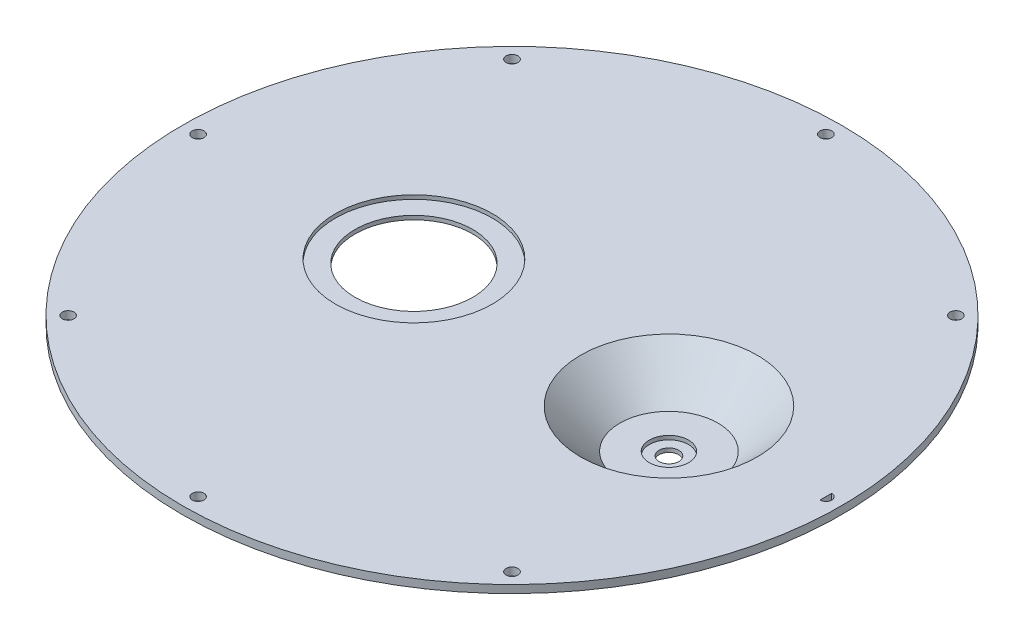
SolidWorks part; units mm, degrees
ref_plane "前视基准面" through (0, 0, 0) normal (0, 0, 1) x (1, 0, 0)
ref_plane "上视基准面" through (0, 0, 0) normal (0, 1, 0) x (1, 0, 0)
ref_plane "右视基准面" through (0, 0, 0) normal (1, 0, 0) x (0, 0, -1)
sketch "草图1" plane through (0, 0, 0) normal (0, 1, 0) x (1, 0, 0)
  circle A0 centre (0, 0) radius 84
  dimension "D1" = 168
extrude "凸台-拉伸1" add sketch "草图1" along normal blind 2
sketch "草图2" plane through (0, 2, 0) normal (0, 1, 0) x (1, 0, 0)
  circle A0 centre (0, 0) radius 80
  circle A1 centre (0, 80) radius 1.5
  circle A2 centre (0, 0) radius 80
  circle A3 centre (56.5685, 56.5685) radius 1.5
  circle A4 centre (0, 0) radius 80
  circle A5 centre (80, 0) radius 1.5
  circle A6 centre (0, 0) radius 80
  circle A7 centre (56.5685, -56.5685) radius 1.5
  circle A8 centre (0, 0) radius 80
  circle A9 centre (0, -80) radius 1.5
  circle A10 centre (0, 0) radius 80
  circle A11 centre (-56.5685, -56.5685) radius 1.5
  circle A12 centre (0, 0) radius 80
  circle A13 centre (-80, 0) radius 1.5
  circle A14 centre (0, 0) radius 80
  circle A15 centre (-56.5685, 56.5685) radius 1.5
  point P28 (0, 0)
  dimension "D1" = 160
  dimension "D2" = 3
  dimension "D3" = 8
extrude "切除-拉伸1" cut sketch "草图2" against normal blind 2 contours A1 | A3 | A5 | A7 | A9 | A11 | A13 | A15
sketch "草图3" plane through (0, 2, 0) normal (0, 1, 0) x (1, 0, 0)
  line L0 (0, 0) -> (40, 0)
  line L1 (0, 0) -> (-25, 0)
  circle A0 centre (-25, 0) radius 15
  circle A1 centre (40, 0) radius 22.5
  dimension "D3" = 30
  dimension "D4" = 45
  dimension "D1" = 40
  dimension "D2" = 25
extrude "切除-拉伸2" cut sketch "草图3" against normal blind 2
sketch "草图4" plane through (0, 2, 0) normal (0, 1, 0) x (1, 0, 0)
  circle A0 centre (-25, 0) radius 20
  dimension "D1" = 40
extrude "切除-拉伸3" cut sketch "草图4" against normal blind 1
sketch "草图6" plane through (0, 0, 0) normal (0, 0, 1) x (1, 0, 0)
  line L0 (0, 2) -> (17.5, 2)
  line L1 (84, 2) -> (-84, 2) construction
  line L2 (17.5, 2) -> (27.4985, -7.9985)
  line L3 (0, 0) -> (16.09, 0)
  line L4 (-84, 0) -> (84, 0) construction
  line L5 (16.09, 0) -> (26.0885, -9.9985)
  line L6 (0, 2) -> (0, 0)
  line L7 (27.4985, -7.9985) -> (34.9985, -7.9985)
  line L8 (37.4985, -9.9985) -> (26.0885, -9.9985)
  line L9 (34.9985, -7.9985) -> (34.9985, -8.9985)
  line L10 (34.9985, -8.9985) -> (37.4985, -8.9985)
  line L12 (37.4985, -9.9985) -> (37.4985, -8.9985)
  line L13 (0, 0) -> (40, 0) construction
  line L14 (40, 0) -> (40, -17.7637)
  dimension "D1" = 17.5
  dimension "D2" = 135
  dimension "D3" = 16.09
  dimension "D4" = 135
  dimension "D5" = 14.14
  dimension "D6" = 14.14
  dimension "D7" = 7.5
  dimension "D8" = 1
  dimension "D9" = 2.5
  dimension "D10" = 40
  dimension "D11" = 9.9985
revolve "旋转1" add sketch "草图6" angle 360 about L14
